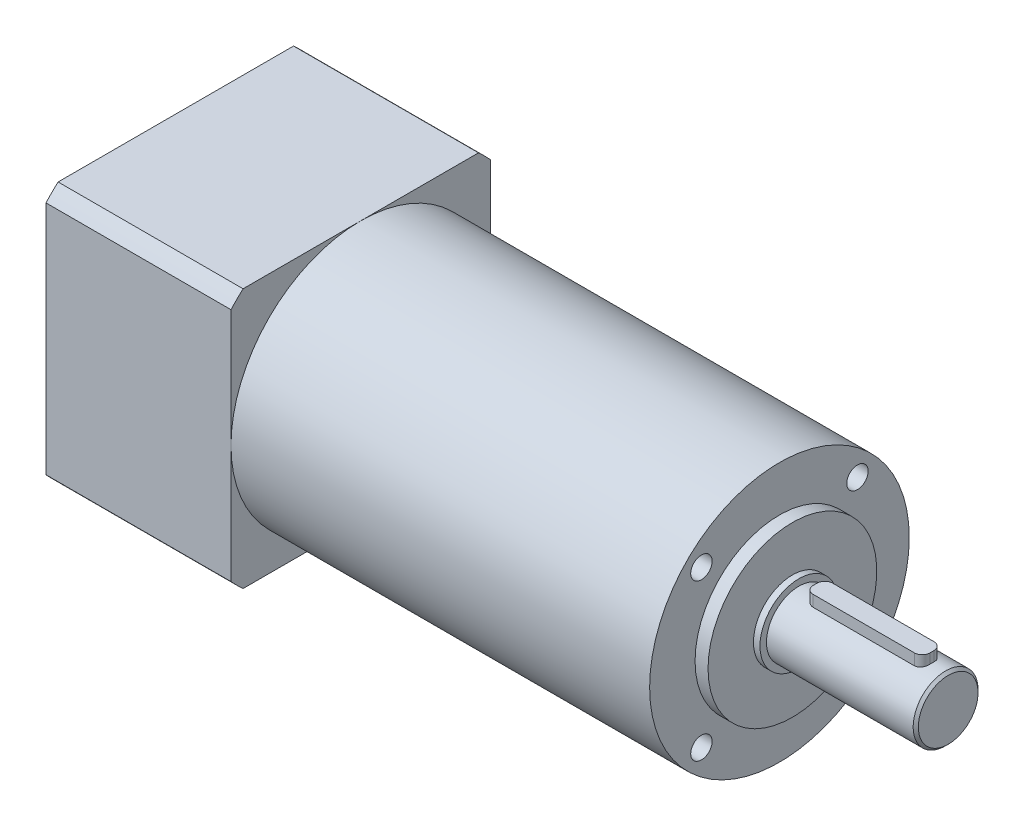
SolidWorks part; units mm, degrees
ref_plane "Front Plane" through (0, 0, 0) normal (0, 0, 1) x (1, 0, 0)
ref_plane "Top Plane" through (0, 0, 0) normal (0, 1, 0) x (1, 0, 0)
ref_plane "Right Plane" through (0, 0, 0) normal (1, 0, 0) x (0, 0, -1)
sketch "Sketch1" plane through (0, 0, 0) normal (0, 0, 1) x (1, 0, 0)
  line L0 (0, 0) -> (90.5, 0) construction
  line L1 (0, 0) -> (0, 20)
  line L2 (0, 20) -> (64.5, 20)
  line L3 (64.5, 20) -> (64.5, 13)
  line L4 (64.5, 13) -> (66.5, 13)
  line L5 (66.5, 13) -> (66.5, 6)
  line L6 (67.5, 5) -> (90.5, 5)
  line L7 (90.5, 5) -> (90.5, 0)
  line L8 (0, 0) -> (90.5, 0) construction
  line L9 (66.5, 6) -> (67.5, 6)
  line L10 (67.5, 6) -> (67.5, 5)
  line L11 (90.5, 0) -> (0, 0)
  dimension "D1" = 40
  dimension "D2" = 64.5
  dimension "D3" = 2
  dimension "D4" = 26
  dimension "D5" = 10
  dimension "D6" = 26
  dimension "D7" = 12
  dimension "D8" = 23
revolve "Revolve1" add sketch "Sketch1" angle 360 about L0
hole_wizard "M4 Tapped Hole1" positions "Sketch3" profile "Sketch5" tap size "M4" standard "ISO"
sketch "Sketch3" plane through (64.5, 0, 0) normal (1, 0, 0) x (0, 0, -1)
  line L1 (-12.0208, -12.0208) -> (12.0208, -12.0208)
  line L2 (-12.0208, -12.0208) -> (-12.0208, 12.0208)
  line L3 (-12.0208, 12.0208) -> (12.0208, 12.0208)
  line L4 (12.0208, -12.0208) -> (12.0208, 12.0208)
  line L5 (-12.0208, -12.0208) -> (12.0208, 12.0208) construction
  line L6 (-12.0208, 12.0208) -> (12.0208, -12.0208) construction
  circle A0 centre (0, 0) radius 17
  point P5 (12.0208, 12.0208)
  point P166 (-12.0208, -12.0208)
  point P167 (-12.0208, 12.0208)
  point P168 (12.0208, -12.0208)
  dimension "D1" = 34
sketch "Sketch5" plane through (64.5, -12.0208, -12.0208) normal (0, 1, 0) x (0, 0, -1)
  line L0 (0, 0) -> (0, 6.9914)
  line L1 (0, 6.9914) -> (1.65, 6)
  line L2 (1.65, 6) -> (1.65, 0)
  line L5 (1.65, 0) -> (0, 0)
  line L10 (0, 6.9914) -> (-1.65, 6) construction
  line L11 (0, -6.35) -> (0, 107.95) construction
  dimension "Tap Drill Dia." = 3.3
  dimension "Tap Drill Depth" = 6
  dimension "Drill Angle" = 118
cosmetic thread "Hole Thread1" parameters "D1"=6, "D2"=4
cosmetic thread "Hole Thread2" parameters "D1"=6, "D2"=4
cosmetic thread "Hole Thread3" parameters "D1"=6, "D2"=4
cosmetic thread "Hole Thread4" parameters "D1"=6, "D2"=4
sketch "Sketch6" plane through (0, 0, 0) normal (-1, 0, 0) x (0, 0, 1)
  line L1 (-20, -20) -> (20, -20)
  line L2 (-20, -20) -> (-20, 20)
  line L3 (-20, 20) -> (20, 20)
  line L4 (20, -20) -> (20, 20)
  line L5 (-20, -20) -> (20, 20) construction
  line L6 (-20, 20) -> (20, -20) construction
  point P0 (0, 0)
  dimension "D1" = 40
extrude "Boss-Extrude1" add sketch "Sketch6" along normal blind 28.5
sketch "Sketch7" plane through (-28.5, 0, 0) normal (-1, 0, 0) x (0, 0, 1)
  line L1 (-20, 20) -> (-20, -20) construction
  line L2 (20, 20) -> (-20, 20) construction
  line L3 (-20, 20) -> (-20, 18.1384)
  line L5 (-18.1384, 20) -> (-20, 20)
  arc A1 (-18.1384, 20) -> (-20, 18.1384) centre (0, 0) ccw
  dimension "D1" = 27
extrude "Cut-Extrude1" cut sketch "Sketch7" against normal up to next
pattern_circular "CirPattern1" count 4 over 360 about axis through (0, 0, 0) along (-1, 0, 0) of "Cut-Extrude1"
chamfer "Chamfer1" distance 0.4 angle 45 1 edges at (90.5, 0, 5)
ref_plane "Plane1" through (0, 5, 0) normal (0, 1, 0) x (1, 0, 0)
sketch "Sketch8" plane through (0, 5, 0) normal (0, 1, 0) x (1, 0, 0)
  line L0 (88, 0) -> (90.1, 0) construction
  line L1 (71.2, 1.5) -> (86.8, 1.5)
  line L2 (70, 0.3) -> (70, -0.3)
  line L3 (71.2, -1.5) -> (86.8, -1.5)
  line L4 (88, 0.3) -> (88, -0.3)
  line L5 (90.1, -5) -> (90.1, 5) construction
  line L6 (90.5, -4.6) -> (90.5, 4.6) construction
  arc A0 (86.8, 1.5) -> (88, 0.3) centre (86.8, 0.3) cw
  arc A1 (86.8, -1.5) -> (88, -0.3) centre (86.8, -0.3) ccw
  arc A2 (70, -0.3) -> (71.2, -1.5) centre (71.2, -0.3) ccw
  arc A3 (71.2, 1.5) -> (70, 0.3) centre (71.2, 0.3) ccw
  point P13 (88, 1.5)
  point P20 (70, 1.5)
  dimension "D4" = 1.2
  dimension "D1" = 18
  dimension "D2" = 2.5
  dimension "D3" = 3
extrude "Boss-Extrude2" add sketch "Sketch8" along normal mid plane 3
move or copy body "Body-Move/Copy1" [suppressed] bodies to move or copy 108
